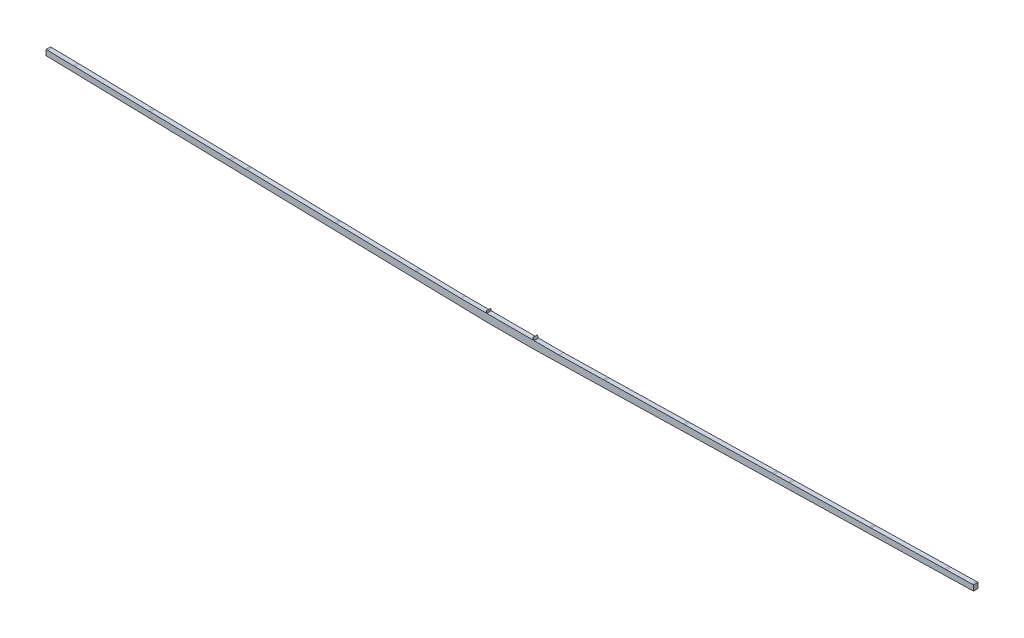
SolidWorks part; units mm, degrees
ref_plane "前视基准面" through (0, 0, 0) normal (0, 0, 1) x (1, 0, 0)
ref_plane "上视基准面" through (0, 0, 0) normal (0, 1, 0) x (1, 0, 0)
ref_plane "右视基准面" through (0, 0, 0) normal (1, 0, 0) x (0, 0, -1)
sketch "Model" plane through (0, 0, 0) normal (0, 0, 1) x (1, 0, 0)
  line L0 (43.8455, -177.4926) -> (538.8103, -165.8562)
  line L1 (43.775, -177.4934) -> (17.8103, -177.4934)
  line L2 (72.9138, -168.9934) -> (122.5606, -168.0091)
  line L3 (421.7966, -162.0486) -> (423.7966, -162.0486)
  line L4 (423.7966, -162.0486) -> (506.4609, -160.2972)
  line L5 (506.4609, -160.2972) -> (508.4609, -160.2972)
  line L6 (536.8103, -159.7762) -> (538.8103, -159.7762)
  line L7 (312.8105, -164.1949) -> (314.8105, -164.1949)
  line L8 (314.8105, -164.1949) -> (330.8105, -163.796)
  line L9 (330.8105, -163.796) -> (332.8105, -163.796)
  line L10 (332.8105, -163.796) -> (421.7966, -162.0486)
  line L11 (212.5914, -166.2048) -> (214.5606, -166.2048)
  line L12 (214.5606, -166.2048) -> (312.8105, -164.1949)
  line L13 (122.5606, -168.0091) -> (124.5606, -168.0091)
  line L14 (124.5606, -168.0091) -> (212.5299, -166.2054)
  line L15 (17.8103, -168.9934) -> (43.775, -168.9934)
  line L16 (43.7803, -166.4905) -> (45.0434, -168.9934)
  line L17 (43.7803, -166.4905) -> (43.775, -168.9934)
  line L18 (45.0434, -168.9934) -> (72.9138, -168.9934)
  line L19 (508.4609, -160.2972) -> (536.8103, -159.7762)
  line L20 (538.8103, -159.7762) -> (538.8103, -165.8562)
  line L21 (-8.225, -177.4926) -> (-503.1897, -165.8562)
  line L22 (-8.1545, -177.4934) -> (17.8103, -177.4934)
  line L23 (-37.2933, -168.9934) -> (-86.9401, -168.0091)
  line L24 (-386.1761, -162.0486) -> (-388.1761, -162.0486)
  line L25 (-388.1761, -162.0486) -> (-470.8404, -160.2972)
  line L26 (-470.8404, -160.2972) -> (-472.8404, -160.2972)
  line L27 (-501.1897, -159.7762) -> (-503.1897, -159.7762)
  line L28 (-277.19, -164.1949) -> (-279.19, -164.1949)
  line L29 (-279.19, -164.1949) -> (-295.19, -163.796)
  line L30 (-295.19, -163.796) -> (-297.19, -163.796)
  line L31 (-297.19, -163.796) -> (-386.1761, -162.0486)
  line L32 (-176.9708, -166.2048) -> (-178.9401, -166.2048)
  line L33 (-178.9401, -166.2048) -> (-277.19, -164.1949)
  line L34 (-86.9401, -168.0091) -> (-88.9401, -168.0091)
  line L35 (-88.9401, -168.0091) -> (-176.9093, -166.2054)
  line L36 (17.8103, -168.9934) -> (-8.1545, -168.9934)
  line L37 (-8.1597, -166.4905) -> (-9.4229, -168.9934)
  line L38 (-8.1597, -166.4905) -> (-8.1545, -168.9934)
  line L39 (-9.4229, -168.9934) -> (-37.2933, -168.9934)
  line L40 (-472.8404, -160.2972) -> (-501.1897, -159.7762)
  line L41 (-503.1897, -159.7762) -> (-503.1897, -165.8562)
  arc A0 (43.775, -177.4934) -> (43.8455, -177.4926) centre (43.775, -174.4934) ccw
  arc A1 (212.5914, -166.2048) -> (212.5299, -166.2054) centre (212.5914, -169.2048) ccw
  arc A2 (-8.225, -177.4926) -> (-8.1545, -177.4934) centre (-8.1545, -174.4934) ccw
  arc A3 (-176.9093, -166.2054) -> (-176.9708, -166.2048) centre (-176.9708, -169.2048) ccw
extrude "凸台-拉伸1" add sketch "Model" along normal blind 5
